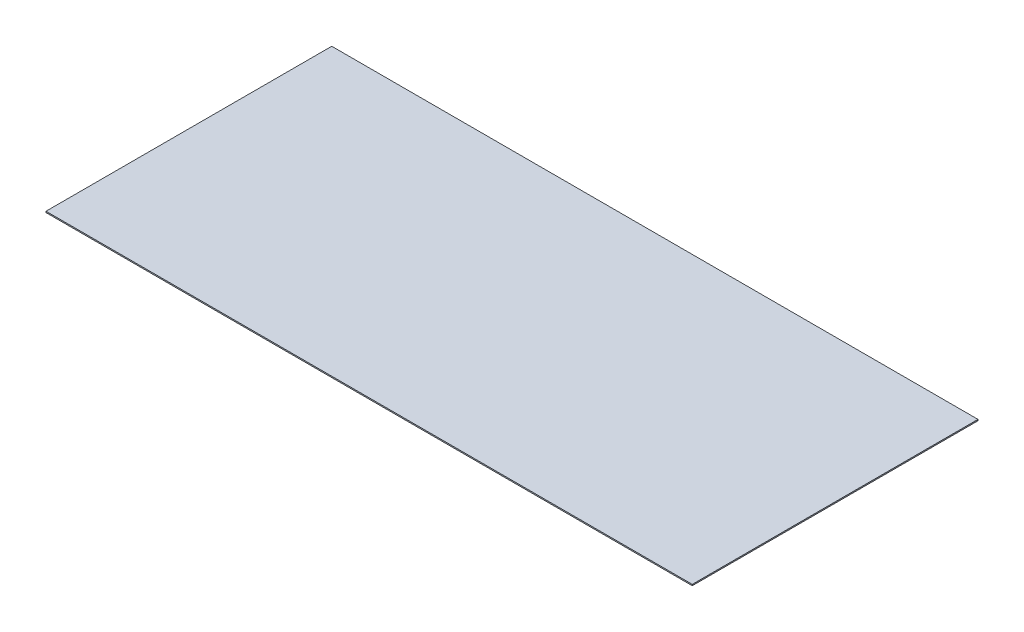
SolidWorks part; units mm, degrees
ref_plane "Front Plane" through (0, 0, 0) normal (0, 0, 1) x (1, 0, 0)
ref_plane "Top Plane" through (0, 0, 0) normal (0, 1, 0) x (1, 0, 0)
ref_plane "Right Plane" through (0, 0, 0) normal (1, 0, 0) x (0, 0, -1)
sketch "Sketch1" plane through (0, 0, 0) normal (0, 1, 0) x (1, 0, 0)
  line L1 (842.5, -372.5) -> (-842.5, -372.5)
  line L2 (842.5, -372.5) -> (842.5, 372.5)
  line L3 (842.5, 372.5) -> (-842.5, 372.5)
  line L4 (-842.5, -372.5) -> (-842.5, 372.5)
  line L5 (842.5, -372.5) -> (-842.5, 372.5) construction
  line L6 (842.5, 372.5) -> (-842.5, -372.5) construction
  point P0 (0, 0)
  dimension "D1" = 745
  dimension "D2" = 1685
extrude "Boss-Extrude1" add sketch "Sketch1" along normal blind 3.175
equation "\"W\"= 1700"
equation "\"L\"= 760"
equation "\"H\"= 810"
equation "\"ARM_BOLT_SPACING\"= 140"
equation "\"ARM_TO_WALL\"= 300"
equation "\"D1@Sketch1\"=\"L\"-15"
equation "\"D2@Sketch1\"=\"W\"-15"
